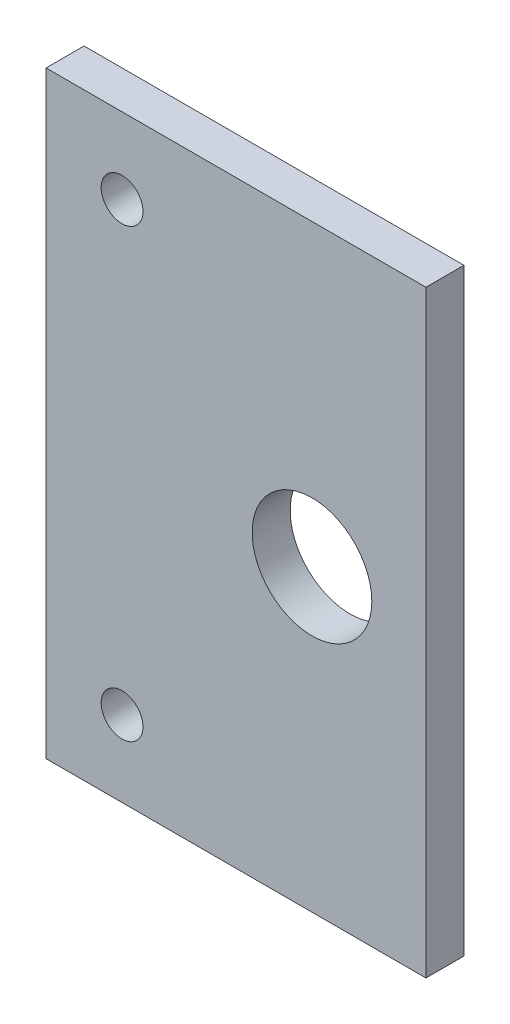
SolidWorks part; units mm, degrees
ref_plane "Front Plane" through (0, 0, 0) normal (0, 0, 1) x (1, 0, 0)
ref_plane "Top Plane" through (0, 0, 0) normal (0, 1, 0) x (1, 0, 0)
ref_plane "Right Plane" through (0, 0, 0) normal (1, 0, 0) x (0, 0, -1)
sketch "Sketch1" plane through (0, 0, 0) normal (0, 0, 1) x (1, 0, 0)
  line L0 (-31.75, 50) -> (31.75, 50) construction
  line L1 (-31.75, 0) -> (31.75, 0)
  line L2 (-31.75, 0) -> (-31.75, 100)
  line L3 (-31.75, 100) -> (31.75, 100)
  line L4 (31.75, 0) -> (31.75, 100)
  line L5 (-6.35, 0) -> (-6.35, 100) construction
  circle A0 centre (-19.05, 12.7) radius 3.5
  circle A1 centre (-19.05, 87.3) radius 3.5
  circle A2 centre (12.7, 50) radius 10
  point P4 (0, 0)
  dimension "D2" = 7
  dimension "D3" = 12.7
  dimension "D4" = 12.7
  dimension "D5" = 20
  dimension "D6" = 19.05
  dimension "D1" = 100
  dimension "D7" = 63.5
  dimension "D8" = 25.4
extrude "Boss-Extrude1" add sketch "Sketch1" along normal blind 6.35
